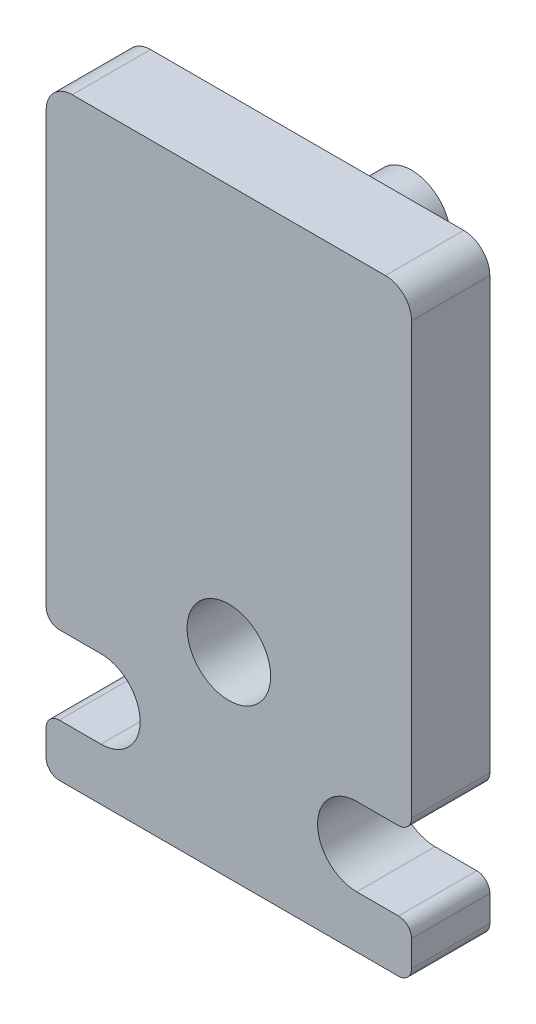
SolidWorks part; units mm, degrees
ref_plane "Alzado" through (0, 0, 0) normal (0, 0, 1) x (1, 0, 0)
ref_plane "Planta" through (0, 0, 0) normal (0, 1, 0) x (1, 0, 0)
ref_plane "Vista lateral" through (0, 0, 0) normal (1, 0, 0) x (0, 0, -1)
sketch "Croquis1" plane through (0, 0, 0) normal (0, 0, 1) x (1, 0, 0)
  line L0 (3, 11.5) -> (7, 11.5)
  line L1 (-7, 11.5) -> (-3, 11.5)
  line L2 (-7, 11.5) -> (-7, -6.5)
  line L3 (-7, -11.5) -> (7, -11.5)
  line L4 (7, 11.5) -> (7, -6.5)
  line L5 (-7, 11.5) -> (7, -11.5) construction
  line L6 (-7, -11.5) -> (7, 11.5) construction
  line L7 (-3, 11.5) -> (3, 11.5)
  line L8 (-3, 11.5) -> (-3, 3.5) construction
  line L9 (-3, 3.5) -> (3, 3.5) construction
  line L10 (3, 11.5) -> (3, 3.5) construction
  line L11 (0, 0) -> (0, -11.5) construction
  line L12 (4.9, -6.5) -> (7, -6.5)
  line L13 (4.9, -9.5) -> (7, -9.5)
  line L14 (-4.9, -6.5) -> (-7, -6.5)
  line L15 (-4.9, -9.5) -> (-7, -9.5)
  line L16 (-7, -9.5) -> (-7, -11.5)
  line L17 (7, -9.5) -> (7, -11.5)
  arc A1 (4.9, -6.5) -> (4.9, -9.5) centre (4.9, -8) ccw
  arc A2 (-4.9, -9.5) -> (-4.9, -6.5) centre (-4.9, -8) ccw
  circle A3 centre (0, -4) radius 1.6
  point P0 (0, 0)
  point P10 (0, 3.5)
  point P14 (-3.4, -8)
  point P16 (3.4, -8)
  point P17 (6.4, -8)
  point P19 (4.9, -9.5)
  point P29 (0, -5.6)
  point P31 (0, 0)
  dimension "D5" = 4
  dimension "D7" = 3
  dimension "D6" = 3.2
  dimension "D1" = 14
  dimension "D2" = 23
  dimension "D3" = 6
  dimension "D4" = 8
  dimension "D8" = 9.8
  dimension "D9" = 2
extrude "Saliente-Extruir1" add sketch "Croquis1" along normal mid plane 3
fillet "Redondeo1" radius 1 2 edges at (-7, 11.5, 0) (7, 11.5, 0)
fillet "Redondeo2" radius 0.5 6 edges at (7, -11.5, 0) (-7, -11.5, 0) (7, -9.5, 0) (7, -6.5, 0) (-7, -9.5, 0) (-7, -6.5, 0)
sketch "Croquis2" plane through (0, 0, -1.5) normal (0, 0, -1) x (-1, 0, 0)
  line L2 (-6, 11.5) -> (6, 11.5) construction
  circle A0 centre (0, 7) radius 1.5
  point P6 (0, 0)
  dimension "D1" = 3
  dimension "D2" = 4.5
extrude "Saliente-Extruir2" add sketch "Croquis2" along normal blind 4
